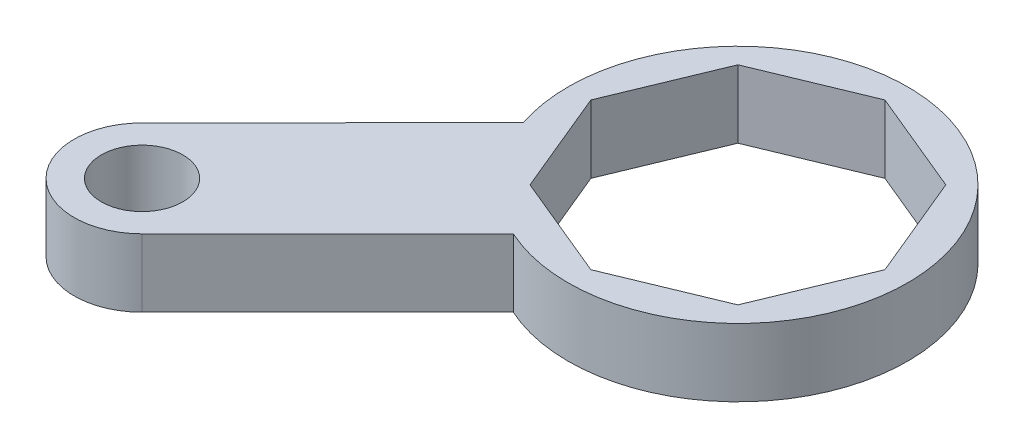
SolidWorks part; units mm, degrees
ref_plane "Front Plane" through (0, 0, 0) normal (0, 0, 1) x (1, 0, 0)
ref_plane "Top Plane" through (0, 0, 0) normal (0, 1, 0) x (1, 0, 0)
ref_plane "Right Plane" through (0, 0, 0) normal (1, 0, 0) x (0, 0, -1)
sketch "Sketch1" plane through (0, 0, 0) normal (0, 1, 0) x (1, 0, 0)
  line L0 (7.6537, 7.6537) -> (-22.3463, -21.5225) construction
  line L1 (0, 10.8239) -> (-7.6537, 7.6537)
  line L2 (-7.6537, 7.6537) -> (-10.8239, 0)
  line L3 (-10.8239, 0) -> (-7.6537, -7.6537)
  line L4 (-7.6537, -7.6537) -> (0, -10.8239)
  line L5 (0, -10.8239) -> (7.6537, -7.6537)
  line L6 (7.6537, -7.6537) -> (10.8239, 0)
  line L7 (10.8239, 0) -> (7.6537, 7.6537)
  line L8 (7.6537, 7.6537) -> (0, 10.8239)
  line L11 (-25.8819, -17.9869) -> (-11.8655, -3.9318)
  line L12 (-18.8108, -25.058) -> (-5.1449, -11.3921)
  arc A0 (-5.1449, -11.3921) -> (-11.8655, -3.9318) centre (0, 0) ccw
  circle A1 centre (0, 0) radius 10 construction
  circle A2 centre (-22.3463, -21.5225) radius 3
  arc A3 (-25.8819, -17.9869) -> (-18.8108, -25.058) centre (-22.3463, -21.5225) ccw
  dimension "D1" = 25
  dimension "D2" = 20
  dimension "D4" = 10
  dimension "D5" = 6
  dimension "D3" = 30
extrude "Boss-Extrude1" add sketch "Sketch1" along normal blind 5
